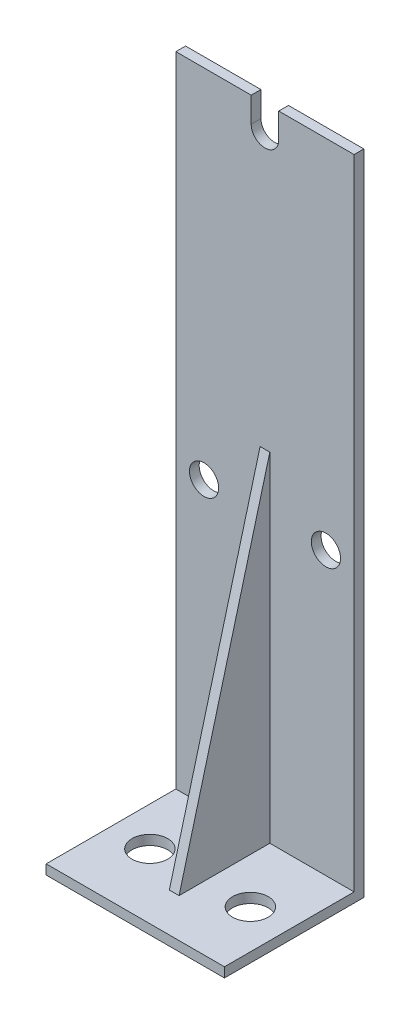
SolidWorks part; units mm, degrees
ref_plane "Płaszczyzna przednia" through (0, 0, 0) normal (0, 0, 1) x (1, 0, 0)
ref_plane "Płaszczyzna górna" through (0, 0, 0) normal (0, 1, 0) x (1, 0, 0)
ref_plane "Płaszczyzna prawa" through (0, 0, 0) normal (1, 0, 0) x (0, 0, -1)
sketch "Szkic1" plane through (0, 0, 0) normal (0, 0, 1) x (1, 0, 0)
  line L1 (0, 0) -> (55, 0)
  line L2 (0, 0) -> (0, 200)
  line L3 (0, 200) -> (55, 200)
  line L4 (55, 0) -> (55, 200)
  dimension "D1" = 55
  dimension "D2" = 200
extrude "Dodanie-wyciągnięcie1" add sketch "Szkic1" along normal mid plane 3
sketch "Szkic2" plane through (0, 0, 1.5) normal (0, 0, 1) x (1, 0, 0)
  line L0 (55, 0) -> (55, 200) construction
  line L1 (0, 0) -> (55, 0)
  line L2 (0, 0) -> (0, 3)
  line L3 (0, 3) -> (55, 3)
  line L4 (55, 0) -> (55, 3)
  dimension "D1" = 3
extrude "Dodanie-wyciągnięcie2" add sketch "Szkic2" along normal blind 40 separate body
sketch "Szkic3" plane through (0, 3, 0) normal (0, 1, 0) x (1, 0, 0)
  line L0 (55, -41.5) -> (0, -41.5) construction
  line L1 (0, -41.5) -> (0, -1.5) construction
  line L2 (12, -21.5) -> (43, -21.5) construction
  line L3 (55, -1.5) -> (0, -1.5) construction
  line L4 (55, -1.5) -> (0, -1.5)
  circle A0 centre (12, -21.5) radius 5.5
  circle A1 centre (43, -21.5) radius 5.5
  point P10 (27.5, -1.5)
  point P11 (27.5, -21.5)
  dimension "D1" = 11
  dimension "D2" = 11
  dimension "D3" = 20
  dimension "D4" = 12
extrude "Wytnij-wyciągnięcie1" cut sketch "Szkic3" against normal blind 20
ref_plane "Płaszczyzna1" through (27.5, 0, 0) normal (1, 0, 0) x (0, 0, -1)
sketch "Szkic4" plane through (27.5, 0, 0) normal (1, 0, 0) x (0, 0, -1)
  line L0 (-29.5, 3) -> (-1.5, 107.4974)
  line L1 (-41.5, 3) -> (-1.5, 3) construction
  line L2 (-1.5, 0) -> (-1.5, 200) construction
  line L3 (-41.5, 3) -> (-1.5, 3)
  line L4 (-1.5, 0) -> (-1.5, 200)
  line L5 (-29.5, 3) -> (-1.5, 3)
  line L6 (-1.5, 3) -> (-1.5, 107.4974)
  dimension "D1" = 15
  dimension "D2" = 28
extrude "Dodanie-wyciągnięcie3" add sketch "Szkic4" along normal mid plane 3 contours L6 L0 L5
sketch "Szkic5" plane through (0, 0, -1.5) normal (0, 0, -1) x (-1, 0, 0)
  line L0 (-31.75, 200) -> (-31.75, 192.25)
  line L1 (-55, 200) -> (0, 200) construction
  line L2 (-23.25, 192.25) -> (-23.25, 200)
  line L3 (-55, 200) -> (0, 200)
  line L4 (-46.3, 90) -> (-8.7, 90) construction
  line L5 (-31.75, 200) -> (-23.25, 200)
  arc A0 (-31.75, 192.25) -> (-23.25, 192.25) centre (-27.5, 192.25) ccw
  circle A1 centre (-8.7, 90) radius 4.5
  circle A2 centre (-46.3, 90) radius 4.5
  point P9 (-27.5, 90)
  point P10 (-27.5, 200)
  dimension "D3" = 9
  dimension "D4" = 9
  dimension "D1" = 8.5
  dimension "D2" = 7.75
  dimension "D5" = 37.6
  dimension "D6" = 110
extrude "Wytnij-wyciągnięcie3" cut sketch "Szkic5" against normal through all
